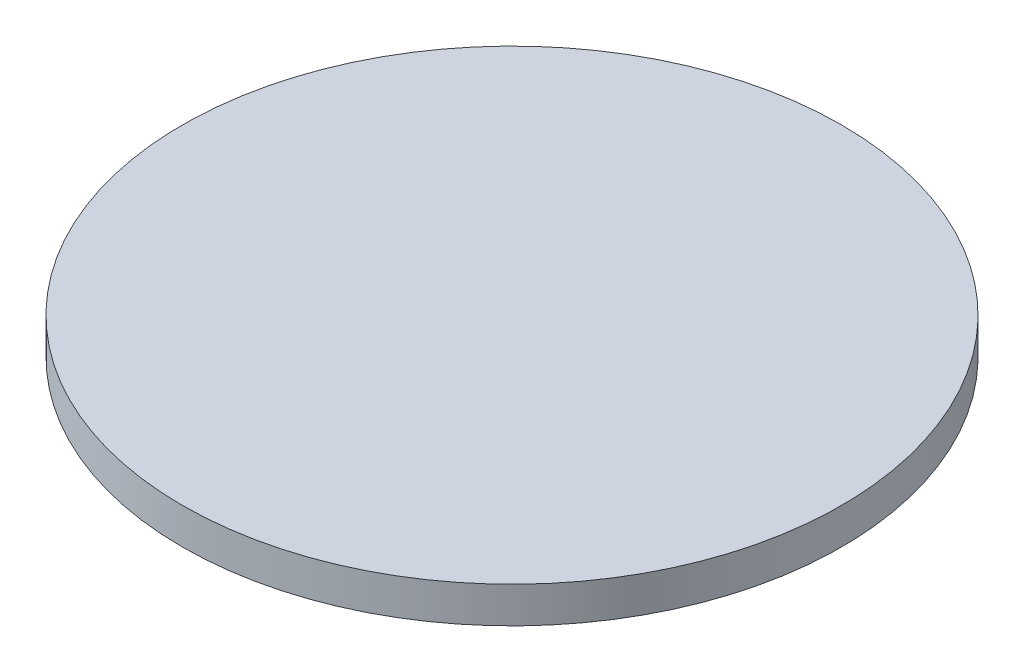
SolidWorks part; units mm, degrees
ref_plane "前基準面" through (0, 0, 0) normal (0, 0, 1) x (1, 0, 0)
ref_plane "上基準面" through (0, 0, 0) normal (0, 1, 0) x (1, 0, 0)
ref_plane "右基準面" through (0, 0, 0) normal (1, 0, 0) x (0, 0, -1)
ref_plane "平面1" through (0, 0, 0) normal (0, 0, -1) x (-1, 0, 0)
sketch "草圖1" plane through (0, 0, 0) normal (0, 0, -1) x (-1, 0, 0)
  line L0 (-137, 28) -> (0, 28)
  line L1 (0, 28) -> (0, 43)
  line L2 (0, 43) -> (-137, 43)
  line L3 (-137, 43) -> (-137, 28)
  line L4 (0, 28) -> (0, 43) construction
revolve "旋轉1" add sketch "草圖1" angle 360 about L4
sketch "草圖2" plane through (0, 28, 0) normal (0, -1, 0) x (1, 0, 0)
  circle A0 centre (0, 0) radius 114.5
extrude "填料-伸長1" add sketch "草圖2" along normal blind 8
sketch "草圖3" plane through (0, 20, 0) normal (0, -1, 0) x (1, 0, 0)
  circle A0 centre (0, 0) radius 82.5
extrude "填料-伸長2" add sketch "草圖3" along normal blind 8
sketch "草圖4" [suppressed] plane through (0, 43, 0) normal (0, 1, 0) x (-1, 0, 0)
  line L0 (40.2772, 72) -> (-40.2772, 72)
  arc A0 (-40.2772, 72) -> (40.2772, 72) centre (0, 0) ccw
